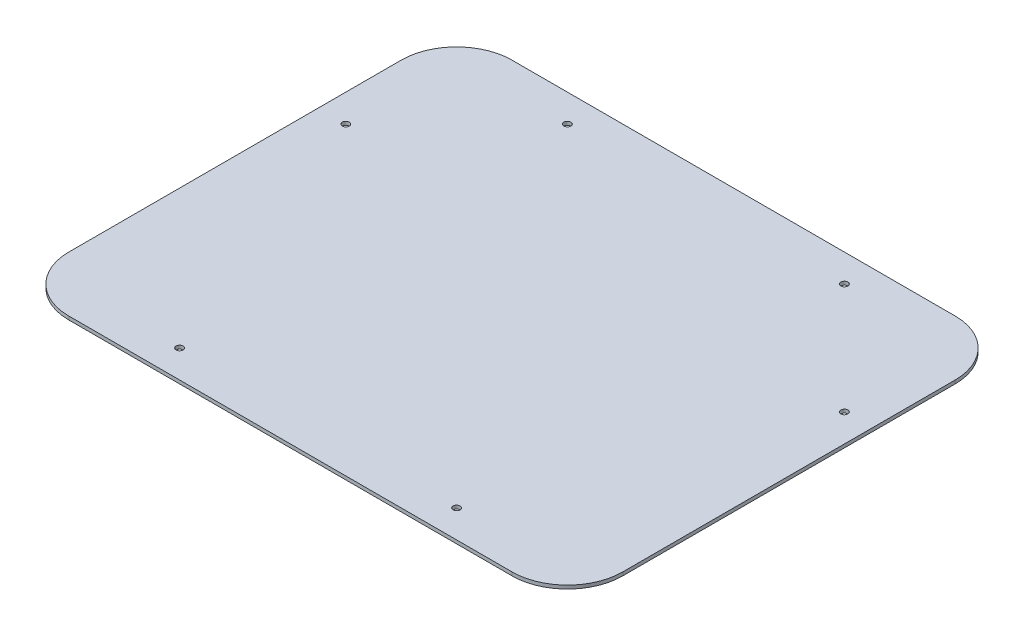
SolidWorks part; units mm, degrees
ref_plane "Front" through (0, 0, 0) normal (0, 0, 1) x (1, 0, 0)
ref_plane "Top" through (0, 0, 0) normal (0, 1, 0) x (1, 0, 0)
ref_plane "Right" through (0, 0, 0) normal (1, 0, 0) x (0, 0, -1)
sketch "Sketch1" plane through (0, 0, 0) normal (0, 1, 0) x (1, 0, 0)
  line L1 (-254, 203.2) -> (254, 203.2)
  line L2 (-254, 203.2) -> (-254, -203.2)
  line L3 (-254, -203.2) -> (254, -203.2)
  line L4 (254, 203.2) -> (254, -203.2)
  point P4 (-254, 0)
  point P6 (0, -203.2)
  dimension "D1" = 406.4
  dimension "D2" = 508
extrude "Boss-Extrude1" add sketch "Sketch1" along normal blind 3.175
fillet "Fillet1" radius 50.8 4 edges at (-254, 1.5875, -203.2) (254, 1.5875, -203.2) (254, 1.5875, 203.2) (-254, 1.5875, 203.2)
hole_wizard "1/4 (0.25) Diameter Hole1" positions "Sketch3" profile "Sketch2" hole size "1/4" standard "Ansi Inch"
sketch "Sketch3" plane through (0, 3.175, 0) normal (0, 1, 0) x (-1, 0, 0)
  line L0 (254, -152.4) -> (254, 152.4) construction
  line L1 (-254, 152.4) -> (-254, -152.4) construction
  line L2 (-203.2, -203.2) -> (203.2, -203.2) construction
  line L3 (203.2, 203.2) -> (-203.2, 203.2) construction
  point P0 (228.6, -76.2)
  point P1 (127, -177.8)
  point P3 (-127, -177.8)
  point P5 (-228.6, -76.2)
  point P7 (-127, 177.8)
  point P9 (127, 177.8)
  dimension "D1" = 127
  dimension "D2" = 127
  dimension "D3" = 127
  dimension "D4" = 25.4
  dimension "D5" = 25.4
  dimension "D6" = 25.4
  dimension "D7" = 25.4
sketch "Sketch2" plane through (-228.6, 3.175, -76.2) normal (1, 0, 0) x (0, 0, 1)
  line L0 (0, 0) -> (0, 27.3077)
  line L1 (0, 27.3077) -> (3.175, 25.4)
  line L2 (3.175, 25.4) -> (3.175, 0)
  line L5 (3.175, 0) -> (0, 0)
  line L10 (0, 27.3077) -> (-3.175, 25.4) construction
  line L11 (0, -6.35) -> (0, 107.95) construction
  dimension "Hole Dia." = 6.35
  dimension "Hole Depth" = 25.4
  dimension "Drill Angle" = 118
